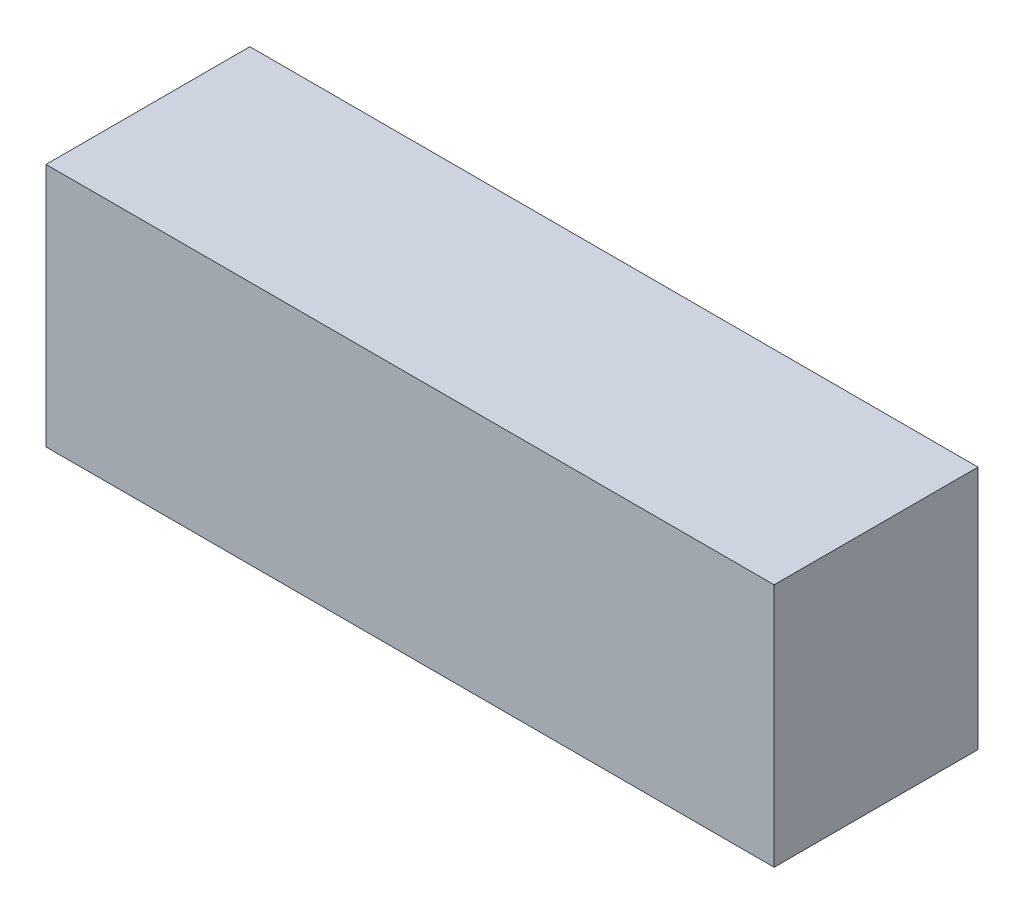
SolidWorks part; units mm, degrees
ref_plane "Plan de face" through (0, 0, 0) normal (0, 0, 1) x (1, 0, 0)
ref_plane "Plan de dessus" through (0, 0, 0) normal (0, 1, 0) x (1, 0, 0)
ref_plane "Plan de droite" through (0, 0, 0) normal (1, 0, 0) x (0, 0, -1)
sketch "Esquisse1" plane through (0, 0, 0) normal (0, 0, 1) x (1, 0, 0)
  line L1 (0, 0) -> (-125, 0)
  line L2 (0, 0) -> (0, 42)
  line L3 (0, 42) -> (-125, 42)
  line L4 (-125, 0) -> (-125, 42)
extrude "Boss.-Extru.1" add sketch "Esquisse1" along normal blind 35
